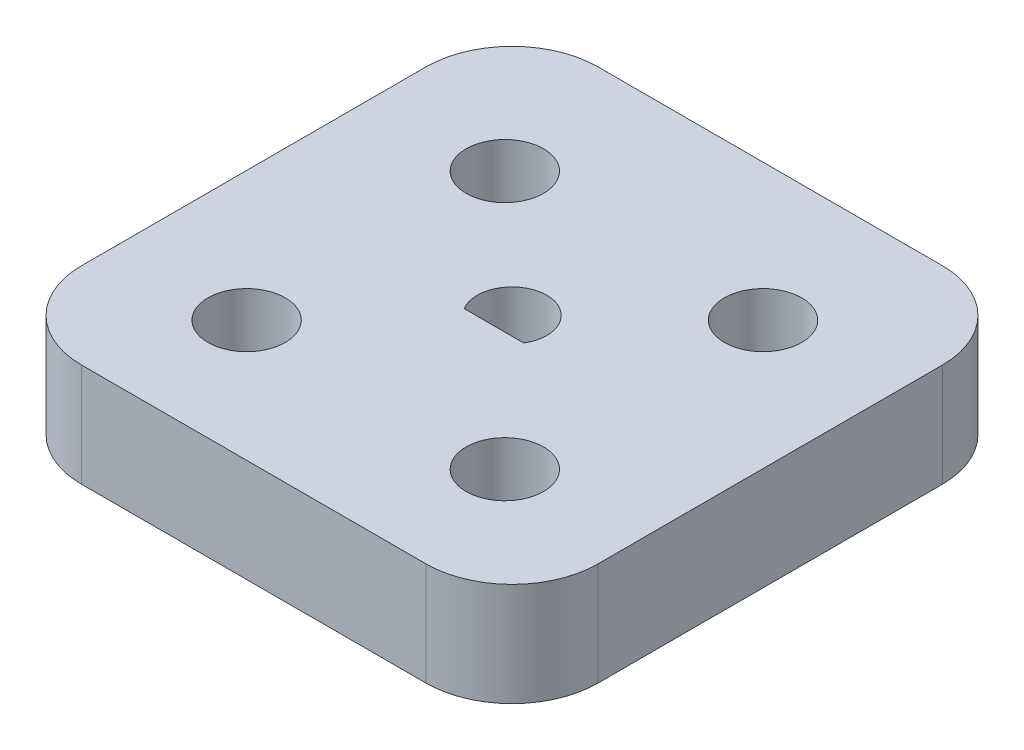
SolidWorks part; units mm, degrees
ref_plane "Front Plane" through (0, 0, 0) normal (0, 0, 1) x (1, 0, 0)
ref_plane "Top Plane" through (0, 0, 0) normal (0, 1, 0) x (1, 0, 0)
ref_plane "Right Plane" through (0, 0, 0) normal (1, 0, 0) x (0, 0, -1)
sketch "Sketch1" plane through (0, 0, 0) normal (0, 1, 0) x (1, 0, 0)
  line L0 (-1.7315, -1.05) -> (1.7315, -1.05)
  line L1 (-15, 15) -> (15, 15)
  line L2 (-15, 15) -> (-15, -15)
  line L3 (-15, -15) -> (15, -15)
  line L4 (15, 15) -> (15, -15)
  line L5 (-15, 15) -> (15, -15) construction
  line L6 (-15, -15) -> (15, 15) construction
  circle A0 centre (0, 0) radius 2.025
  point P0 (0, 0)
  dimension "D2" = 4.05
  dimension "D1" = 30
  dimension "D3" = 1.05
extrude "Boss-Extrude1" add sketch "Sketch1" along normal blind 6 contours L4 L1 L2 L3 A0 | L0 A0
fillet "Fillet1" radius 5 4 edges at (-15, 3, -15) (15, 3, -15) (-15, 3, 15) (15, 3, 15)
hole_wizard "#8 Clearance Hole1" positions "Sketch2" profile "Sketch3" hole size "#8" standard "ANSI Inch" end condition through all
sketch "Sketch2" plane through (0, 6, 0) normal (0, 1, 0) x (1, 0, 0)
  point P0 (-7.4677, 7.0516)
  point P2 (7.5323, 7.0516)
  point P4 (-7.4677, -7.9484)
  point P6 (7.5323, -7.9484)
  dimension "D1" = 15
  dimension "D2" = 15
sketch "Sketch3" plane through (-7.4677, 6, -7.0516) normal (1, 0, 0) x (0, 0, 1)
  line L0 (0, 0) -> (0, 6)
  line L1 (0, 6) -> (2.2479, 6)
  line L2 (2.2479, 6) -> (2.2479, 0)
  line L5 (2.2479, 0) -> (0, 0)
  line L11 (0, -6.35) -> (0, 107.95) construction
  dimension "Thru Hole Dia." = 4.4958
  dimension "Thru Hole Depth" = 6
equation "\"D2@Sketch2\"=\"D1@Sketch2\""
